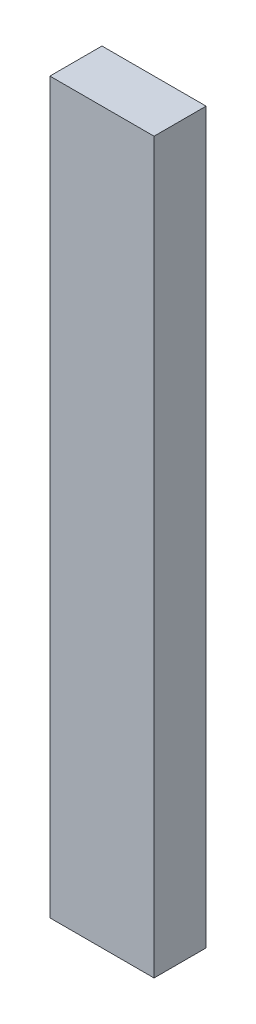
SolidWorks part; units mm, degrees
ref_plane "Front Plane" through (0, 0, 0) normal (0, 0, 1) x (1, 0, 0)
ref_plane "Top Plane" through (0, 0, 0) normal (0, 1, 0) x (1, 0, 0)
ref_plane "Right Plane" through (0, 0, 0) normal (1, 0, 0) x (0, 0, -1)
sketch "Sketch1" plane through (0, 0, 0) normal (0, 1, 0) x (1, 0, 0)
  line L1 (12.7, -6.35) -> (-12.7, -6.35)
  line L2 (12.7, -6.35) -> (12.7, 6.35)
  line L3 (12.7, 6.35) -> (-12.7, 6.35)
  line L4 (-12.7, -6.35) -> (-12.7, 6.35)
  line L5 (12.7, -6.35) -> (-12.7, 6.35) construction
  line L6 (12.7, 6.35) -> (-12.7, -6.35) construction
  point P0 (0, 0)
  dimension "D1" = 12.7
  dimension "D2" = 6.35
extrude "Boss-Extrude1" add sketch "Sketch1" along normal blind 177.8
